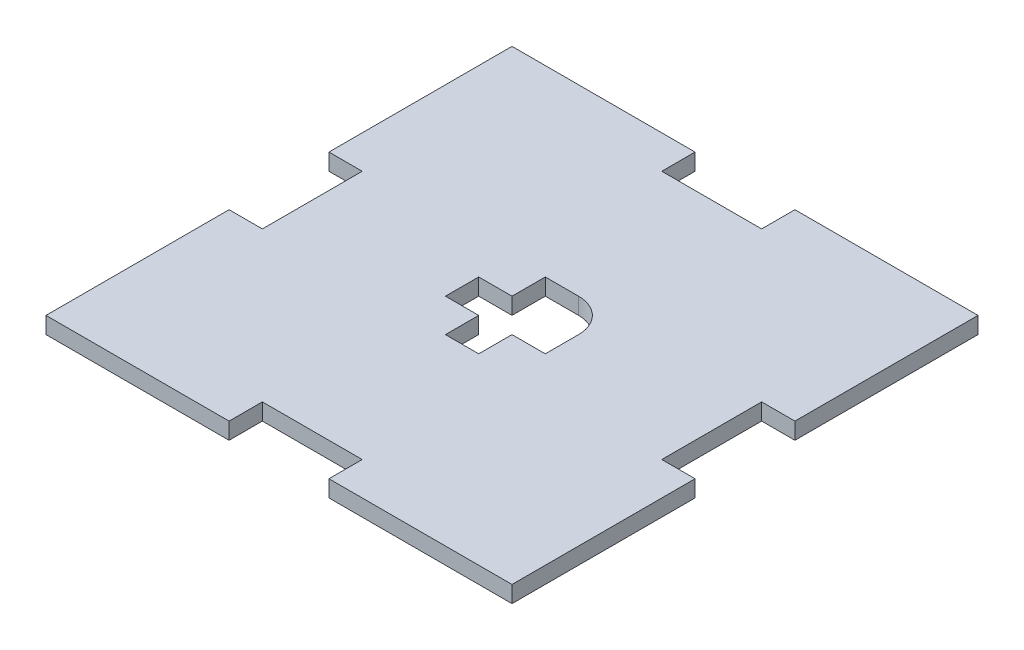
SolidWorks part; units mm, degrees
ref_plane "Front Plane" through (0, 0, 0) normal (0, 0, 1) x (1, 0, 0)
ref_plane "Top Plane" through (0, 0, 0) normal (0, 1, 0) x (1, 0, 0)
ref_plane "Right Plane" through (0, 0, 0) normal (1, 0, 0) x (0, 0, -1)
sketch "Sketch1" plane through (0, 0, 0) normal (0, 1, 0) x (1, 0, 0)
  line L1 (0, 0) -> (88.9, 0)
  line L2 (0, 0) -> (0, 88.9)
  line L3 (0, 88.9) -> (88.9, 88.9)
  line L4 (88.9, 0) -> (88.9, 88.9)
  dimension "D1" = 88.9
  dimension "D2" = 88.9
extrude "Boss-Extrude1" add sketch "Sketch1" along normal blind 3.175
sketch "Sketch5" plane through (0, 3.175, 0) normal (0, 1, 0) x (1, 0, 0)
  line L0 (44.45, 88.9) -> (44.45, 0) construction
  line L1 (41.275, 47.625) -> (41.275, 53.975)
  line L2 (34.925, 41.275) -> (41.275, 41.275)
  line L3 (34.925, 41.275) -> (34.925, 47.625)
  line L4 (34.925, 47.625) -> (41.275, 47.625)
  line L5 (53.975, 41.275) -> (53.975, 47.625)
  line L6 (34.925, 41.275) -> (53.975, 47.625) construction
  line L7 (0, 44.45) -> (88.9, 44.45) construction
  line L8 (34.925, 47.625) -> (53.975, 41.275) construction
  line L9 (47.625, 34.925) -> (41.275, 34.925)
  line L10 (47.625, 34.925) -> (47.625, 41.275)
  line L11 (47.625, 53.975) -> (41.275, 53.975)
  line L12 (41.275, 34.925) -> (41.275, 41.275)
  line L13 (47.625, 34.925) -> (41.275, 53.975) construction
  line L14 (47.625, 53.975) -> (41.275, 34.925) construction
  line L15 (47.625, 41.275) -> (53.975, 41.275)
  line L16 (88.9, 88.9) -> (0, 88.9) construction
  line L17 (88.9, 0) -> (88.9, 88.9) construction
  line L18 (0, -1.7463) -> (0, 1.7463) construction
  line L19 (-1.7463, 0) -> (1.7463, 0) construction
  line L20 (47.625, 47.625) -> (47.625, 53.975)
  line L21 (47.625, 47.625) -> (53.975, 47.625)
  point P0 (44.45, 44.45)
  point P16 (42.8625, 44.45)
  point P17 (44.45, 44.45)
  point P23 (41.275, 47.625)
  point P24 (47.625, 47.625)
  point P25 (47.625, 41.275)
  point P26 (41.275, 41.275)
  dimension "D1" = 19.05
  dimension "D2" = 6.35
  dimension "D3" = 19.05
  dimension "D4" = 6.35
extrude "Cut-Extrude3" cut sketch "Sketch5" against normal blind 3.175
sketch "Sketch4" plane through (0, 3.175, 0) normal (0, 1, 0) x (1, 0, 0)
  line L0 (88.9, 88.9) -> (0, 88.9) construction
  line L1 (34.925, 88.9) -> (53.975, 88.9)
  line L2 (34.925, 88.9) -> (34.925, 82.55)
  line L3 (34.925, 82.55) -> (53.975, 82.55)
  line L4 (53.975, 88.9) -> (53.975, 82.55)
  line L5 (88.9, 0) -> (88.9, 88.9) construction
  line L6 (-1.7463, 0) -> (1.7463, 0) construction
  line L7 (88.9, 53.975) -> (82.55, 53.975)
  line L8 (88.9, 53.975) -> (88.9, 34.925)
  line L9 (82.55, 53.975) -> (82.55, 34.925)
  line L10 (88.9, 34.925) -> (82.55, 34.925)
  line L11 (53.975, 0) -> (53.975, 6.35)
  line L12 (53.975, 0) -> (34.925, 0)
  line L13 (53.975, 6.35) -> (34.925, 6.35)
  line L14 (34.925, 0) -> (34.925, 6.35)
  line L15 (0, 34.925) -> (6.35, 34.925)
  line L16 (0, 34.925) -> (0, 53.975)
  line L17 (6.35, 34.925) -> (6.35, 53.975)
  line L18 (0, 53.975) -> (6.35, 53.975)
  line L20 (88.9, 44.45) -> (0, 44.45) construction
  line L21 (0, -1.7463) -> (0, 1.7463) construction
  line L22 (44.45, 0) -> (44.45, 88.9) construction
  point P8 (50.8, 38.1)
  point P11 (44.45, 88.9)
  point P19 (88.9, 44.45)
  point P24 (44.45, 0)
  point P29 (0, 44.45)
  point P30 (44.45, 44.45)
  point P34 (44.45, 44.45)
  dimension "D1" = 6.35
  dimension "D2" = 19.05
  dimension "D4" = 38.1
  dimension "D5" = 38.1
  dimension "D6" = 4
extrude "Cut-Extrude2" cut sketch "Sketch4" against normal blind 3.175
sketch "Sketch7" plane through (0, 3.175, 0) normal (0, 1, 0) x (1, 0, 0)
  line L0 (41.275, 53.975) -> (53.975, 53.975) construction
  line L1 (53.975, 41.275) -> (53.975, 53.975) construction
  line L3 (53.975, 53.975) -> (47.625, 53.975)
  line L4 (53.975, 53.975) -> (53.975, 47.625)
  line L5 (53.975, 47.625) -> (47.625, 47.625)
  line L6 (47.625, 53.975) -> (47.625, 47.625)
extrude "Cut-Extrude4" cut sketch "Sketch7" against normal through all
fillet "Fillet1" radius 6.35 1 edges at (53.975, 1.5875, -53.975)
